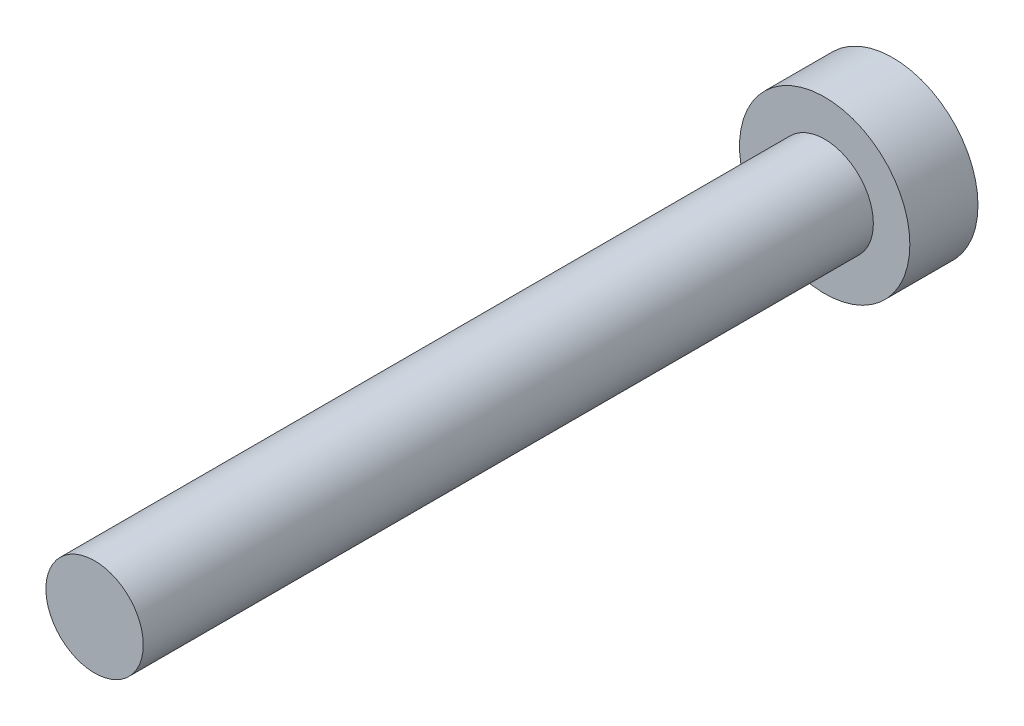
SolidWorks part; units mm, degrees
ref_plane "Front Plane" through (0, 0, 0) normal (0, 0, 1) x (1, 0, 0)
ref_plane "Top Plane" through (0, 0, 0) normal (0, 1, 0) x (1, 0, 0)
ref_plane "Right Plane" through (0, 0, 0) normal (1, 0, 0) x (0, 0, -1)
sketch "S01 - Low socket head" plane through (0, 0, 0) normal (0, 0, 1) x (1, 0, 0)
  circle A0 centre (0, 0) radius 3.5
  dimension "D1" = 7
extrude "01 - Low socket head" add sketch "S01 - Low socket head" along normal blind 2.8 from offset 2.8
sketch "S02 - Nominal M4 shank" plane through (0, 0, 0) normal (0, 0, 1) x (1, 0, 0)
  circle A0 centre (0, 0) radius 2
  dimension "D1" = 4
extrude "02 - Nominal M4 shank" add sketch "S02 - Nominal M4 shank" along normal blind 30
sketch "S03 - Hex drive recess" plane through (0, 0, 0) normal (0, 0, 1) x (1, 0, 0)
  line L0 (1.4434, 0) -> (0.7217, 1.25)
  line L1 (0.7217, 1.25) -> (-0.7217, 1.25)
  line L2 (-0.7217, 1.25) -> (-1.4434, 0)
  line L3 (-1.4434, 0) -> (-0.7217, -1.25)
  line L4 (-0.7217, -1.25) -> (0.7217, -1.25)
  line L5 (0.7217, -1.25) -> (1.4434, 0)
  dimension "D1" = 0.7217
  dimension "D2" = 1.4434
  dimension "D3" = 0.7217
  dimension "D4" = 1.4434
  dimension "D5" = 1.25
  dimension "D6" = 1.25
extrude "03 - Hex drive recess" cut sketch "S03 - Hex drive recess" along normal blind 1.65 from offset 2.9
